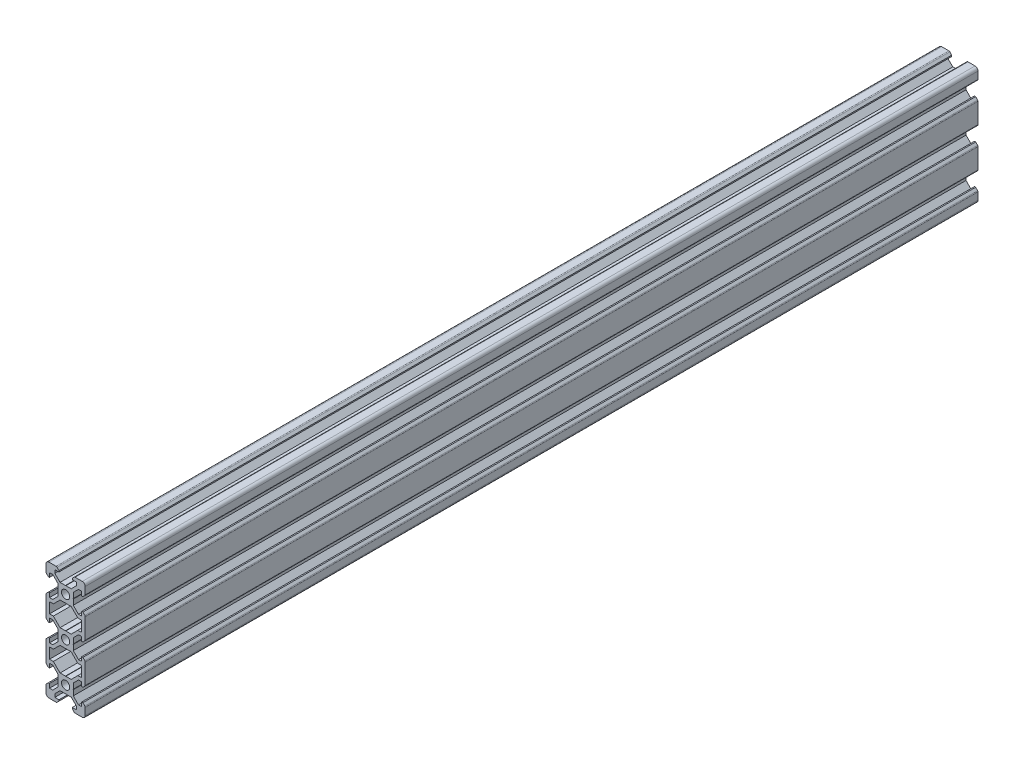
SolidWorks part; units mm, degrees
material "6063-T5"
ref_plane "Front" through (0, 0, 0) normal (0, 0, 1) x (1, 0, 0)
ref_plane "Top" through (0, 0, 0) normal (0, 1, 0) x (1, 0, 0)
ref_plane "Right" through (0, 0, 0) normal (1, 0, 0) x (0, 0, -1)
sketch "Sketch1" plane through (0, 0, 0) normal (0, 0, 1) x (1, 0, 0)
  line L0 (-8.5, 10) -> (-10, 8.5) construction
  line L1 (-8.5, 10) -> (-4.8628, 10)
  line L2 (-10, 8.5) -> (-10, 4.8628)
  line L3 (25.9287, -20) -> (-28.3599, -20) construction
  line L4 (10, 8.5) -> (10, 4.8628)
  line L5 (-10, 10) -> (10, -10) construction
  line L6 (-10, -10) -> (10, 10) construction
  line L7 (8.2, -5.5) -> (8.2, -3.3865)
  line L8 (-8.2, -5.5) -> (-8.2, -3.3865)
  line L9 (-5.5, 8.2) -> (-3.3865, 8.2)
  line L10 (-8.2, -12.7) -> (-8.2, -7.3)
  line L11 (-3.9005, 2.8395) -> (-6.561, 5.5)
  line L12 (-6.561, 5.5) -> (-8.2, 5.5)
  line L13 (-2.8395, -3.9005) -> (-0.1, -3.9005)
  line L14 (-3.9005, -2.8395) -> (-3.9005, -0.1)
  line L15 (-2.8395, 3.9005) -> (-0.1, 3.9005)
  line L16 (3.9005, -2.8395) -> (3.9005, -0.1)
  line L17 (-8.2, 3.3865) -> (-8.81, 3.3865)
  line L18 (-8.81, 3.3865) -> (-9.7976, 4.3741)
  line L19 (8.5, 10) -> (10, 8.5) construction
  line L20 (-2.8395, 3.9005) -> (-5.5, 6.561)
  line L21 (-5.5, 6.561) -> (-5.5, 8.2)
  line L22 (-3.3865, 8.2) -> (-3.3865, 8.81)
  line L23 (-3.3865, 8.81) -> (-4.3741, 9.7976)
  line L24 (0, 24.069) -> (0, -33.8154) construction
  line L25 (3.3865, 8.81) -> (4.3741, 9.7976)
  line L26 (3.3865, 8.2) -> (3.3865, 8.81)
  line L27 (5.5, 6.561) -> (5.5, 8.2)
  line L28 (2.8395, 3.9005) -> (5.5, 6.561)
  line L29 (3.3865, 8.2) -> (5.5, 8.2)
  line L30 (4.8628, 10) -> (8.5, 10)
  line L31 (-0.1, 3.9005) -> (0, 3.8005)
  line L32 (0.1, 3.9005) -> (0, 3.8005)
  line L33 (0.1, 3.9005) -> (2.8395, 3.9005)
  line L34 (25.9287, 0) -> (-28.3459, 0) construction
  line L35 (-0.1, -3.9005) -> (0, -3.8005)
  line L36 (0.1, -3.9005) -> (0, -3.8005)
  line L37 (0.1, -3.9005) -> (2.8395, -3.9005)
  line L38 (-3.9005, 0.1) -> (-3.8005, 0)
  line L39 (-3.8005, 0) -> (-3.9005, -0.1)
  line L40 (-3.9005, 0.1) -> (-3.9005, 2.8395)
  line L41 (3.9005, 0.1) -> (3.8005, 0)
  line L42 (3.8005, 0) -> (3.9005, -0.1)
  line L43 (3.9005, 0.1) -> (3.9005, 2.8395)
  line L44 (8.81, 3.3865) -> (9.7976, 4.3741)
  line L45 (8.2, 3.3865) -> (8.81, 3.3865)
  line L46 (6.561, 5.5) -> (8.2, 5.5)
  line L47 (3.9005, 2.8395) -> (6.561, 5.5)
  line L48 (2.8395, -3.9005) -> (5.5, -6.561)
  line L49 (3.9005, -2.8395) -> (6.561, -5.5)
  line L50 (-2.8395, -3.9005) -> (-5.5, -6.561)
  line L51 (-3.9005, -2.8395) -> (-6.561, -5.5)
  line L52 (6.561, -5.5) -> (8.2, -5.5)
  line L53 (-6.561, -5.5) -> (-8.2, -5.5)
  line L54 (-8.81, -3.3865) -> (-9.7976, -4.3741)
  line L55 (-8.2, -3.3865) -> (-8.81, -3.3865)
  line L56 (8.81, -3.3865) -> (9.7976, -4.3741)
  line L57 (8.2, -3.3865) -> (8.81, -3.3865)
  line L58 (8.2, 3.3865) -> (8.2, 5.5)
  line L59 (10, -4.8628) -> (10, -15.1372)
  line L60 (-8.2, 3.3865) -> (-8.2, 5.5)
  line L61 (-10, -4.8628) -> (-10, -15.1372)
  line L62 (-28.3459, -10) -> (-10, -10) construction
  line L63 (-3.9005, -20.1) -> (-3.9005, -22.8395)
  line L64 (-3.9005, -20.1) -> (-3.8005, -20)
  line L65 (-3.8005, -20) -> (-3.9005, -19.9)
  line L66 (3.9005, -20.1) -> (3.9005, -22.8395)
  line L67 (3.9005, -20.1) -> (3.8005, -20)
  line L68 (3.8005, -20) -> (3.9005, -19.9)
  line L69 (6.561, -14.5) -> (8.2, -14.5)
  line L70 (3.9005, -17.1605) -> (6.561, -14.5)
  line L71 (3.9005, -17.1605) -> (3.9005, -19.9)
  line L72 (-3.9005, -17.1605) -> (-3.9005, -19.9)
  line L73 (-3.9005, -17.1605) -> (-6.561, -14.5)
  line L74 (-6.561, -14.5) -> (-8.2, -14.5)
  line L75 (-8.2, -16.6135) -> (-8.81, -16.6135)
  line L76 (-8.81, -16.6135) -> (-9.7976, -15.6259)
  line L77 (8.2, -16.6135) -> (8.81, -16.6135)
  line L78 (8.81, -16.6135) -> (9.7976, -15.6259)
  line L79 (-2.8395, -16.0995) -> (-5.5, -13.439)
  line L80 (-2.8395, -16.0995) -> (-0.1, -16.0995)
  line L81 (-0.1, -16.0995) -> (0, -16.1995)
  line L82 (0.1, -16.0995) -> (0, -16.1995)
  line L83 (0.1, -16.0995) -> (2.8395, -16.0995)
  line L84 (2.8395, -16.0995) -> (5.5, -13.439)
  line L85 (-8.2, -16.6135) -> (-8.2, -14.5)
  line L86 (8.2, -16.6135) -> (8.2, -14.5)
  line L87 (2.8395, -23.9005) -> (5.5, -26.561)
  line L88 (-2.8395, -23.9005) -> (-5.5, -26.561)
  line L89 (-0.1, -23.9005) -> (0, -23.8005)
  line L90 (0.1, -23.9005) -> (0, -23.8005)
  line L91 (0.1, -23.9005) -> (2.8395, -23.9005)
  line L92 (-2.8395, -23.9005) -> (-0.1, -23.9005)
  line L93 (-8.2, -23.3865) -> (-8.2, -25.5)
  line L94 (-8.2, -23.3865) -> (-8.81, -23.3865)
  line L95 (-8.81, -23.3865) -> (-9.7976, -24.3741)
  line L96 (8.2, -23.3865) -> (8.2, -25.5)
  line L97 (8.2, -23.3865) -> (8.81, -23.3865)
  line L98 (8.81, -23.3865) -> (9.7976, -24.3741)
  line L99 (8.2, -27.3) -> (8.2, -32.7)
  line L100 (10, -35.1372) -> (10, -24.8628)
  line L101 (-10, -35.1372) -> (-10, -24.8628)
  line L102 (-8.2, -27.3) -> (-8.2, -32.7)
  line L103 (3.9005, -22.8395) -> (6.561, -25.5)
  line L104 (-3.9005, -22.8395) -> (-6.561, -25.5)
  line L105 (6.239, -27.3) -> (8.2, -27.3)
  line L106 (-6.239, -27.3) -> (-8.2, -27.3)
  line L107 (-6.561, -25.5) -> (-8.2, -25.5)
  line L108 (6.561, -25.5) -> (8.2, -25.5)
  line L109 (5.5, -26.561) -> (6.239, -27.3)
  line L110 (-5.5, -26.561) -> (-6.239, -27.3)
  line L111 (8.2, -34.5) -> (8.2, -36.6135)
  line L112 (8.2, -36.6135) -> (8.81, -36.6135)
  line L113 (8.81, -36.6135) -> (9.7976, -35.6259)
  line L114 (-8.2, -34.5) -> (-8.2, -36.6135)
  line L115 (-6.239, -7.3) -> (-8.2, -7.3)
  line L116 (-5.5, -6.561) -> (-6.239, -7.3)
  line L117 (6.239, -7.3) -> (8.2, -7.3)
  line L118 (5.5, -6.561) -> (6.239, -7.3)
  line L119 (-6.239, -12.7) -> (-8.2, -12.7)
  line L120 (-5.5, -13.439) -> (-6.239, -12.7)
  line L121 (5.5, -13.439) -> (6.239, -12.7)
  line L122 (6.239, -12.7) -> (8.2, -12.7)
  line L123 (8.2, -12.7) -> (8.2, -7.3)
  line L124 (-8.2, -36.6135) -> (-8.81, -36.6135)
  line L125 (10, -10) -> (25.9287, -10) construction
  line L126 (-8.81, -36.6135) -> (-9.7976, -35.6259)
  line L128 (-0.1, -36.0995) -> (0, -36.1995)
  line L129 (0.1, -36.0995) -> (0, -36.1995)
  line L130 (0.1, -36.0995) -> (2.8395, -36.0995)
  line L131 (-6.561, -34.5) -> (-8.2, -34.5)
  line L132 (6.561, -34.5) -> (8.2, -34.5)
  line L133 (6.239, -32.7) -> (8.2, -32.7)
  line L134 (-6.239, -32.7) -> (-8.2, -32.7)
  line L135 (-5.5, -33.439) -> (-6.239, -32.7)
  line L136 (5.5, -33.439) -> (6.239, -32.7)
  line L137 (-8.81, -43.3865) -> (-9.7976, -44.3741)
  line L138 (-8.2, -43.3865) -> (-8.81, -43.3865)
  line L139 (-8.2, -43.3865) -> (-8.2, -45.5)
  line L140 (-6.561, -45.5) -> (-8.2, -45.5)
  line L141 (-10, -48.5) -> (-10, -44.8628)
  line L142 (-8.5, -50) -> (-4.8628, -50)
  line L143 (-3.3865, -48.81) -> (-4.3741, -49.7976)
  line L144 (-3.3865, -48.2) -> (-3.3865, -48.81)
  line L145 (-5.5, -48.2) -> (-3.3865, -48.2)
  line L146 (-5.5, -46.561) -> (-5.5, -48.2)
  line L147 (3.3865, -48.2) -> (5.5, -48.2)
  line L148 (3.3865, -48.2) -> (3.3865, -48.81)
  line L149 (3.3865, -48.81) -> (4.3741, -49.7976)
  line L150 (4.8628, -50) -> (8.5, -50)
  line L151 (5.5, -46.561) -> (5.5, -48.2)
  line L152 (6.561, -45.5) -> (8.2, -45.5)
  line L153 (8.2, -43.3865) -> (8.2, -45.5)
  line L154 (10, -48.5) -> (10, -44.8628)
  line L155 (8.81, -43.3865) -> (9.7976, -44.3741)
  line L156 (8.2, -43.3865) -> (8.81, -43.3865)
  line L157 (-0.1, -43.9005) -> (0, -43.8005)
  line L158 (0.1, -43.9005) -> (0, -43.8005)
  line L159 (-2.8395, -43.9005) -> (-0.1, -43.9005)
  line L160 (0.1, -43.9005) -> (2.8395, -43.9005)
  line L161 (3.9005, -40.1) -> (3.8005, -40)
  line L162 (3.8005, -40) -> (3.9005, -39.9)
  line L163 (3.9005, -37.1605) -> (3.9005, -39.9)
  line L164 (3.9005, -40.1) -> (3.9005, -42.8395)
  line L165 (-2.8395, -36.0995) -> (-0.1, -36.0995)
  line L166 (-2.8395, -43.9005) -> (-5.5, -46.561)
  line L167 (-3.9005, -37.1605) -> (-3.9005, -39.9)
  line L168 (-3.8005, -40) -> (-3.9005, -39.9)
  line L169 (-3.9005, -40.1) -> (-3.8005, -40)
  line L170 (-3.9005, -42.8395) -> (-6.561, -45.5)
  line L171 (2.8395, -43.9005) -> (5.5, -46.561)
  line L172 (3.9005, -42.8395) -> (6.561, -45.5)
  line L173 (3.9005, -37.1605) -> (6.561, -34.5)
  line L174 (2.8395, -36.0995) -> (5.5, -33.439)
  line L175 (-3.9005, -42.8395) -> (-3.9005, -40.1)
  line L176 (-6.561, -34.5) -> (-3.9005, -37.1605)
  line L177 (-5.5, -33.439) -> (-2.8395, -36.0995)
  circle A0 centre (0, 0) radius 2.1
  arc A1 (-8.5, 10) -> (-10, 8.5) centre (-8.5, 8.5) ccw
  arc A2 (10, 8.5) -> (8.5, 10) centre (8.5, 8.5) ccw
  arc A3 (-4.3741, 9.7976) -> (-4.8628, 10) centre (-4.8628, 9.3088) ccw
  arc A4 (4.8628, 10) -> (4.3741, 9.7976) centre (4.8628, 9.3088) ccw
  circle A5 centre (0, -20) radius 2.1
  arc A6 (9.7976, 4.3741) -> (10, 4.8628) centre (9.3088, 4.8628) ccw
  arc A7 (-10, 4.8628) -> (-9.7976, 4.3741) centre (-9.3088, 4.8628) ccw
  arc A8 (-10, -4.8628) -> (-9.7976, -4.3741) centre (-9.3088, -4.8628) cw
  arc A9 (9.7976, -4.3741) -> (10, -4.8628) centre (9.3088, -4.8628) cw
  arc A10 (-10, -15.1372) -> (-9.7976, -15.6259) centre (-9.3088, -15.1372) ccw
  arc A11 (9.7976, -15.6259) -> (10, -15.1372) centre (9.3088, -15.1372) ccw
  arc A12 (-10, -24.8628) -> (-9.7976, -24.3741) centre (-9.3088, -24.8628) cw
  arc A13 (9.7976, -24.3741) -> (10, -24.8628) centre (9.3088, -24.8628) cw
  arc A14 (9.7976, -35.6259) -> (10, -35.1372) centre (9.3088, -35.1372) ccw
  arc A15 (-10, -35.1372) -> (-9.7976, -35.6259) centre (-9.3088, -35.1372) ccw
  circle A16 centre (0, -40) radius 2.1
  arc A17 (-10, -44.8628) -> (-9.7976, -44.3741) centre (-9.3088, -44.8628) cw
  arc A18 (-8.5, -50) -> (-10, -48.5) centre (-8.5, -48.5) cw
  arc A19 (-4.3741, -49.7976) -> (-4.8628, -50) centre (-4.8628, -49.3088) cw
  arc A20 (4.8628, -50) -> (4.3741, -49.7976) centre (4.8628, -49.3088) cw
  arc A21 (10, -48.5) -> (8.5, -50) centre (8.5, -48.5) cw
  arc A22 (9.7976, -44.3741) -> (10, -44.8628) centre (9.3088, -44.8628) cw
  point P17 (-9.25, 9.25)
  point P21 (9.25, 9.25)
  dimension "D2" = 4.2
  dimension "D4" = 1.5
  dimension "D3" = 20
  dimension "D5" = 0.529
  dimension "D6" = 6.773
  dimension "D7" = 90
  dimension "D8" = 11
  dimension "D9" = 0.61
  dimension "D10" = 0.1
  dimension "D11" = 0.1
  dimension "D12" = 0.1
  dimension "D13" = 0.1
  dimension "D14" = 5.679
  dimension "D15" = 1.639
  dimension "D16" = 1.8
  dimension "D17" = 90
  dimension "D18" = 6.773
  dimension "D19" = 90
  dimension "D20" = 20
  dimension "D21" = 1.8
extrude "Boss-Extrude2" add sketch "Sketch1" along normal blind 455
equation "\"base-xwidth\" = 455mm"
equation "\"base-yheight\"= 500mm"
equation "\"base-zdepth\"= 500mm"
equation "\"D1@Boss-Extrude2\"=\"base-xwidth\""
